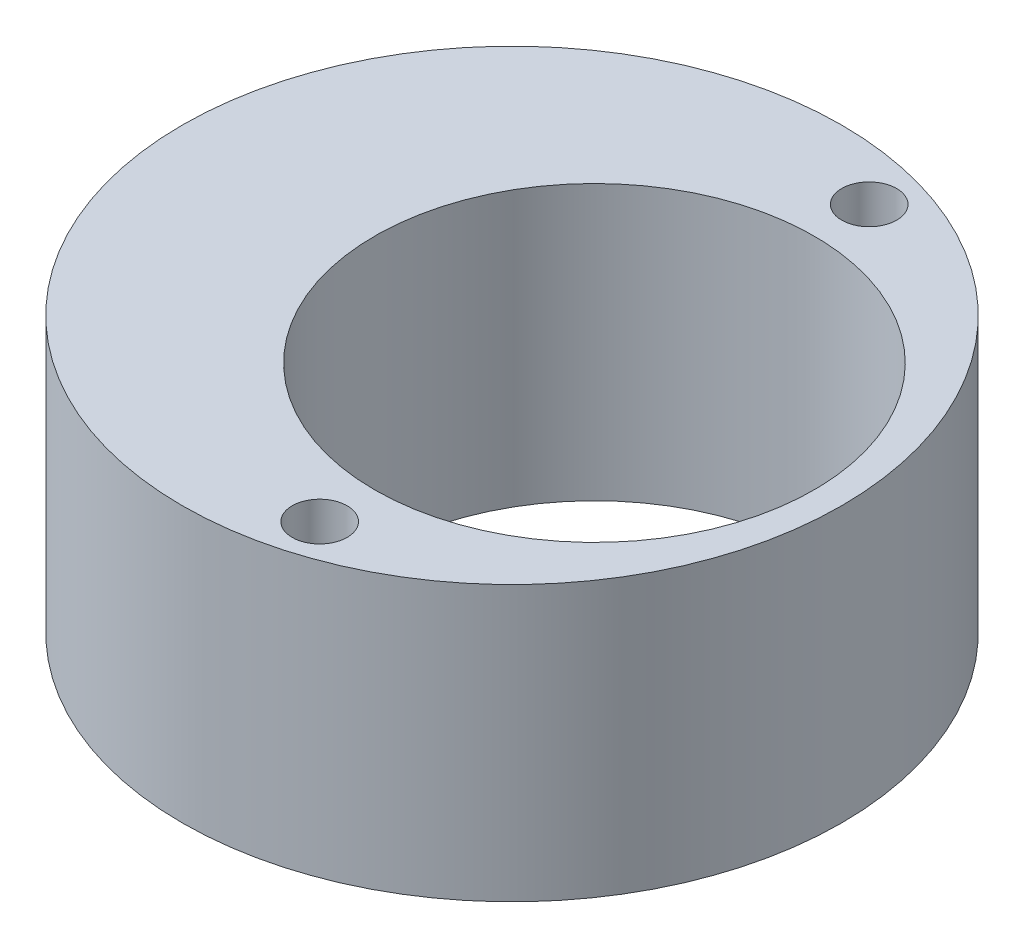
SolidWorks part; units mm, degrees
ref_plane "Front Plane" through (0, 0, 0) normal (0, 0, 1) x (1, 0, 0)
ref_plane "Top Plane" through (0, 0, 0) normal (0, 1, 0) x (1, 0, 0)
ref_plane "Right Plane" through (0, 0, 0) normal (1, 0, 0) x (0, 0, -1)
sketch "Sketch1" plane through (0, 0, 0) normal (0, 1, 0) x (1, 0, 0)
  line L0 (0, 0) -> (-1.5, 0) construction
  line L1 (0, 8.6459) -> (0, -10.0098) construction
  circle A0 centre (0, 0) radius 4
  circle A1 centre (-1.5, 0) radius 6
  circle A4 centre (0, 5) radius 0.5
  circle A5 centre (0, -5) radius 0.5
  dimension "D1" = 8
  dimension "D3" = 12
  dimension "D4" = 1
  dimension "D2" = 1.5
  dimension "D5" = 5
  dimension "D6" = 5
extrude "Boss-Extrude1" add sketch "Sketch1" along normal blind 5
